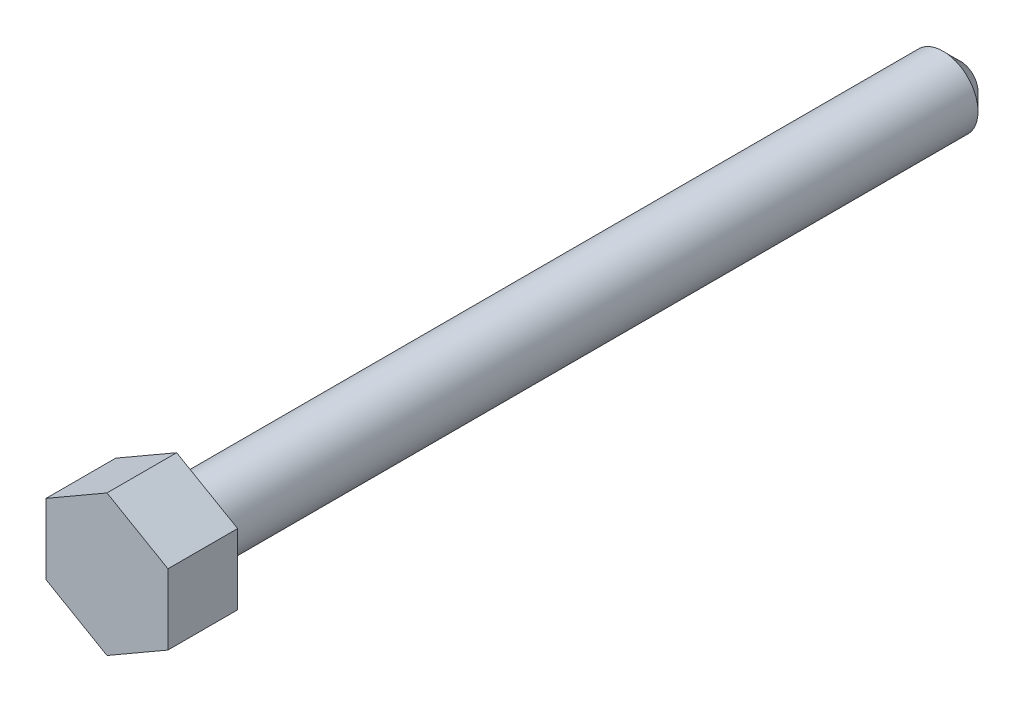
SolidWorks part; units mm, degrees
ref_plane "Front Plane" through (0, 0, 0) normal (0, 0, 1) x (1, 0, 0)
ref_plane "Top Plane" through (0, 0, 0) normal (0, 1, 0) x (1, 0, 0)
ref_plane "Right Plane" through (0, 0, 0) normal (1, 0, 0) x (0, 0, -1)
sketch "Sketch1" plane through (0, 0, 0) normal (0, 0, 1) x (1, 0, 0)
  circle A0 centre (0, 0) radius 2
  dimension "D1" = 4
extrude "Стержень" add sketch "Sketch1" along normal blind 45
sketch "Sketch2" plane through (0, 0, 45) normal (0, 0, 1) x (1, 0, 0)
  line L1 (0, 4.0415) -> (-3.5, 2.0207)
  line L2 (-3.5, 2.0207) -> (-3.5, -2.0207)
  line L3 (-3.5, -2.0207) -> (0, -4.0415)
  line L4 (0, -4.0415) -> (3.5, -2.0207)
  line L5 (3.5, -2.0207) -> (3.5, 2.0207)
  line L6 (3.5, 2.0207) -> (0, 4.0415)
  circle A0 centre (0, 0) radius 3.5 construction
  point P1 (0, 0)
  dimension "D1" = 7
extrude "Голова" add sketch "Sketch2" along normal blind 4
chamfer "Chamfer1" distance 1 angle 45 1 edges at (2, 0, 0)
